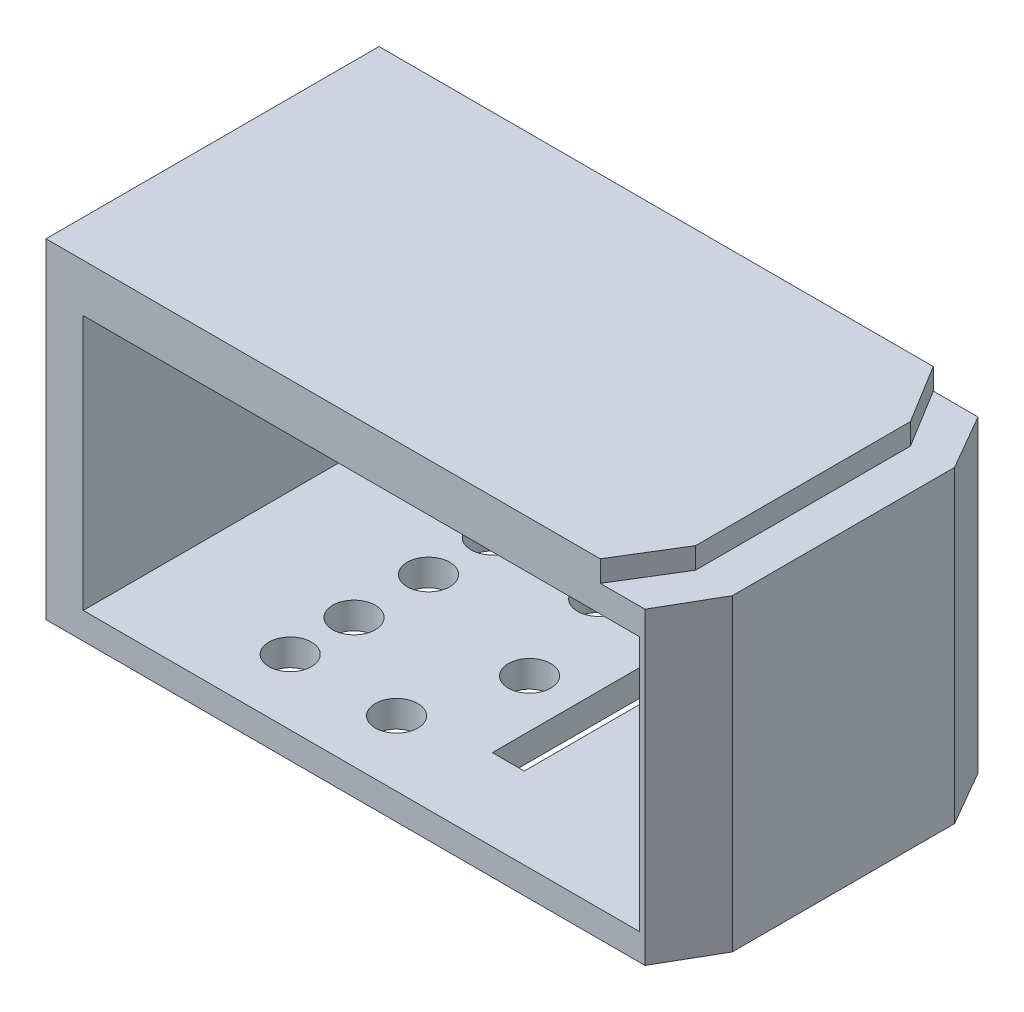
SolidWorks part; units mm, degrees
ref_plane "Plano frontal" through (0, 0, 0) normal (0, 0, 1) x (1, 0, 0)
ref_plane "Plano superior" through (0, 0, 0) normal (0, 1, 0) x (1, 0, 0)
ref_plane "Plano direito" through (0, 0, 0) normal (1, 0, 0) x (0, 0, -1)
sketch "Vista Frontal" plane through (0, 0, 0) normal (0, 0, 1) x (1, 0, 0)
  line L1 (-26.15, 12) -> (26.15, 12)
  line L2 (-26.15, 12) -> (-26.15, -12)
  line L3 (-26.15, -12) -> (26.15, -12)
  line L4 (26.15, 12) -> (26.15, -12)
  line L5 (-26.15, 12) -> (26.15, -12) construction
  line L6 (-26.15, -12) -> (26.15, 12) construction
  line L7 (-29.65, 14.5) -> (29.65, 14.5)
  line L8 (-29.65, 14.5) -> (-29.65, -14.5)
  line L9 (-29.65, -14.5) -> (29.65, -14.5)
  line L10 (29.65, 14.5) -> (29.65, -14.5)
  line L11 (-29.65, 14.5) -> (29.65, -14.5) construction
  line L12 (-29.65, -14.5) -> (29.65, 14.5) construction
  point P0 (0, 0)
  point P6 (0, 0)
  dimension "D1" = 2.5
  dimension "D2" = 29
  dimension "D3" = 3.5
  dimension "D4" = 59.3
extrude "Corpo do Modulo" add sketch "Vista Frontal" along normal mid plane 31.3
sketch "Esboço3" plane through (0, 14.5, 0) normal (0, 1, 0) x (1, 0, 0)
  line L0 (-29.65, -15.65) -> (-29.65, 15.65) construction
  line L1 (26.6478, -15.65) -> (29.65, -10.45)
  line L2 (-29.65, -15.65) -> (29.65, -15.65) construction
  line L3 (29.65, -15.65) -> (29.65, 15.65) construction
  line L4 (29.65, -10.45) -> (29.65, -15.65)
  line L5 (29.65, -15.65) -> (26.6478, -15.65)
  line L6 (29.65, 0) -> (-29.65, 0) construction
  line L7 (29.65, 15.65) -> (26.6478, 15.65)
  line L8 (29.65, 10.45) -> (29.65, 15.65)
  line L9 (26.6478, 15.65) -> (29.65, 10.45)
  circle A0 centre (-29.65, 0) radius 2.3
  dimension "D1" = 4.6
  dimension "D2" = 60
  dimension "D3" = 5.2
extrude "Padrão de Encaixe" cut sketch "Esboço3" against normal through all
sketch "Esboço4" plane through (0, -14.5, 0) normal (0, -1, 0) x (1, 0, 0)
  line L0 (-27.35, 0) -> (29.65, 0) construction
  line L1 (29.65, 10.45) -> (29.65, -10.45) construction
  line L2 (-29.65, -2.3) -> (-29.65, -15.65) construction
  line L3 (-2.85, 9.5) -> (-29.65, 9.5) construction
  line L4 (-29.65, 15.65) -> (-29.65, 2.3) construction
  line L5 (-12.85, 9.5) -> (-12.85, 0) construction
  line L7 (4.65, 8) -> (7.65, 8)
  line L8 (4.65, 8) -> (4.65, -8)
  line L9 (4.65, -8) -> (7.65, -8)
  line L10 (7.65, 8) -> (7.65, -8)
  line L11 (4.65, 8) -> (7.65, -8) construction
  line L12 (4.65, -8) -> (7.65, 8) construction
  arc A0 (-29.65, -2.3) -> (-29.65, 2.3) centre (-29.65, 0) ccw construction
  circle A1 centre (0.15, 0) radius 2
  circle A2 centre (-2.85, 9.5) radius 2
  circle A3 centre (-12.85, 9.5) radius 2
  circle A4 centre (-12.85, 3.5) radius 2
  circle A5 centre (-12.85, -3.5) radius 2
  circle A6 centre (-12.85, -9.5) radius 2
  circle A7 centre (-2.85, -9.5) radius 2
  point P23 (6.15, 0)
  dimension "D1" = 4
  dimension "D2" = 4
  dimension "D3" = 29.8
  dimension "D4" = 9.5
  dimension "D5" = 3
  dimension "D6" = 4
  dimension "D7" = 4
  dimension "D8" = 10
  dimension "D9" = 6
  dimension "D10" = 16
  dimension "D11" = 3
  dimension "D12" = 4.5
extrude "Furos Internos" cut sketch "Esboço4" against normal blind 3.6
sketch "Extra Tampa" plane through (0, 14.5, 0) normal (0, 1, 0) x (1, 0, 0)
  line L0 (29.65, 0) -> (-28.0001, 0) construction
  line L1 (29.65, -10.45) -> (29.65, 10.45) construction
  line L2 (0, 15.65) -> (0, -15.65) construction
  line L3 (26.6478, 15.65) -> (-29.65, 15.65) construction
  line L4 (26.6478, -15.65) -> (-29.65, -15.65) construction
  line L5 (22.4436, 16) -> (22.4436, -16) construction
  line L6 (-29.65, 15.65) -> (22.4436, 15.65)
  line L7 (-29.65, 15.65) -> (-29.65, -15.65)
  line L8 (22.4436, 15.65) -> (25.85, 10.1)
  line L9 (25.85, 10.1) -> (25.85, -10.1)
  line L10 (25.85, -10.1) -> (22.4436, -15.65)
  line L11 (22.4436, -15.65) -> (-29.65, -15.65)
  arc A0 (-30, -1.9999) -> (-30, 1.9999) centre (-30, 0) ccw construction
extrude "Calço Superior" add sketch "Extra Tampa" along normal blind 2
sketch "Furo Compensador" plane through (0, 14.5, 0) normal (0, -1, 0) x (1, 0, 0)
  line L0 (-29.65, -2.3) -> (-29.65, 2.3) construction
  circle A0 centre (-29.65, 0) radius 2.3
  arc A1 (-29.65, -2.3) -> (-29.65, 2.3) centre (-29.65, 0) ccw construction
  dimension "D1" = 0
extrude "Corte compensador" cut sketch "Furo Compensador" against normal blind 0.5
